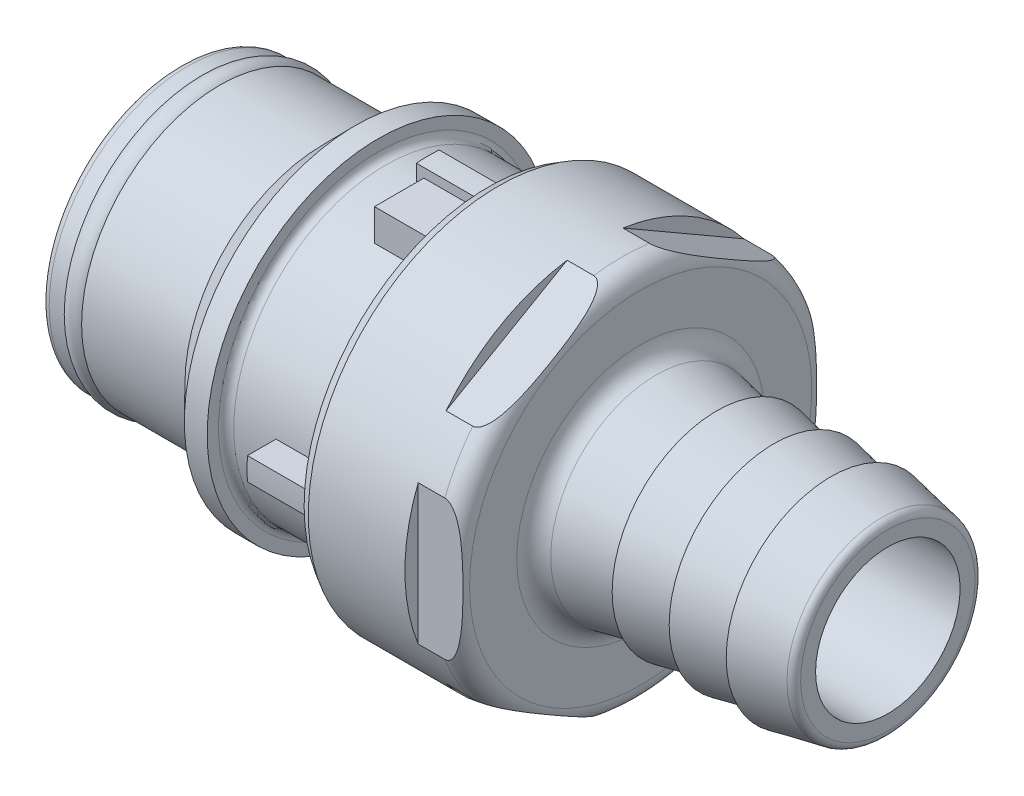
SolidWorks part; units mm, degrees
ref_plane "Front" through (0, 0, 0) normal (0, 0, 1) x (1, 0, 0)
ref_plane "Top" through (0, 0, 0) normal (0, 1, 0) x (1, 0, 0)
ref_plane "Right" through (0, 0, 0) normal (1, 0, 0) x (0, 0, -1)
ref_plane "Plane1" through (0, 0, 0) normal (0, 0, -1) x (-1, 0, 0)
sketch "Sketch1" plane through (0, 0, 0) normal (0, 0, -1) x (-1, 0, 0)
  line L0 (21.4503, 0) -> (19.6723, 0) construction
  arc A0 (19.6723, 8.7884) -> (21.4503, 8.7884) centre (20.5613, 9.0835) ccw
  arc A1 (21.4503, 8.7884) -> (19.6723, 8.7884) centre (20.5613, 8.5007) ccw
revolve "Revolve1" add sketch "Sketch1" angle 360 about L0
ref_plane "Plane2" through (0, 0, 0) normal (0, 0, -1) x (-1, 0, 0)
sketch "Sketch2" plane through (0, 0, 0) normal (0, 0, -1) x (-1, 0, 0)
  line L0 (0, 8.382) -> (9.558, 8.382)
  line L1 (9.558, 8.382) -> (9.558, 7.3614)
  line L2 (9.558, 7.3614) -> (11.7652, 7.3614)
  line L3 (11.7652, 7.3614) -> (12.2025, 6.604)
  line L4 (12.2025, 6.604) -> (22.6568, 6.604)
  line L5 (22.6568, 6.604) -> (22.6568, 8.7249)
  line L6 (22.1488, 9.2329) -> (13.081, 9.2329)
  line L7 (13.081, 9.2329) -> (10.922, 11.43)
  line L8 (10.922, 11.43) -> (9.398, 11.43)
  line L9 (9.398, 11.43) -> (9.398, 10.668)
  line L10 (8.89, 10.16) -> (3.302, 10.16)
  line L11 (2.032, 11.43) -> (2.032, 12.3187)
  line L12 (2.032, 12.3187) -> (1.3716, 12.7)
  line L13 (1.3716, 12.7) -> (0, 12.7)
  line L14 (0, 12.7) -> (0, 8.382)
  line L15 (22.6818, 0) -> (-22.225, 0) construction
  arc A0 (22.6568, 8.7249) -> (22.1488, 9.2329) centre (22.1488, 8.7249) ccw
  arc A1 (9.398, 10.668) -> (8.89, 10.16) centre (8.89, 10.668) cw
  arc A2 (3.302, 10.16) -> (2.032, 11.43) centre (3.302, 11.43) cw
revolve "Revolve2" add sketch "Sketch2" angle 360 about L15
ref_plane "Plane3" through (0, 0, 0) normal (0, 0, 1) x (1, 0, 0)
sketch "Sketch3" plane through (0, 0, 0) normal (0, 0, 1) x (1, 0, 0)
  line L0 (-25.4, 0) -> (-25.4, 2.159)
  line L1 (-25.4, 2.159) -> (-23.749, 2.159)
  line L2 (-21.717, 4.191) -> (-21.717, 4.572)
  line L3 (-21.336, 4.953) -> (-21.209, 4.953)
  line L4 (-21.209, 4.953) -> (-21.209, 3.8862)
  line L5 (-20.701, 3.3782) -> (-18.923, 3.3782)
  line L6 (-18.415, 3.8862) -> (-18.415, 5.6896)
  line L7 (-18.415, 5.6896) -> (-16.7132, 7.3914)
  line L8 (-16.7132, 7.3914) -> (-10.668, 7.3914)
  line L9 (-10.668, 7.3914) -> (-9.906, 8.1534)
  line L10 (-9.906, 8.1534) -> (0.254, 8.1534)
  line L11 (0.254, 8.1534) -> (0.254, 7.747)
  line L12 (0.254, 7.747) -> (-0.508, 6.985)
  line L13 (-0.508, 6.985) -> (-9.1443, 6.985)
  line L14 (-9.1443, 6.985) -> (-9.144, 5.715)
  line L15 (-9.144, 5.715) -> (-12.446, 5.715)
  line L16 (-12.446, 5.715) -> (-14.6002, 4.2066)
  line L17 (-14.2004, 1.9396) -> (-9.7088, 0.736)
  line L18 (-9.144, 0) -> (-25.4, 0)
  line L19 (-9.144, 0) -> (-25.4, 0) construction
  arc A0 (-23.749, 2.159) -> (-21.717, 4.191) centre (-23.749, 4.191) ccw
  arc A1 (-21.717, 4.572) -> (-21.336, 4.953) centre (-21.336, 4.572) cw
  arc A2 (-21.209, 3.8862) -> (-20.701, 3.3782) centre (-20.701, 3.8862) ccw
  arc A3 (-18.923, 3.3782) -> (-18.415, 3.8862) centre (-18.923, 3.8862) ccw
  arc A4 (-14.6002, 4.2066) -> (-14.2004, 1.9396) centre (-13.8717, 3.1663) ccw
  arc A5 (-9.7088, 0.736) -> (-9.144, 0) centre (-9.906, 0) cw
revolve "Revolve3" add sketch "Sketch3" angle 360 about L19
ref_plane "Plane4" through (-2.032, 0, 0) normal (-1, 0, 0) x (0, 0, 1)
sketch "Sketch4" plane through (-2.032, 0, 0) normal (-1, 0, 0) x (0, 0, 1)
  line L0 (-0.762, -10.1314) -> (-0.762, -12.0409)
  line L1 (0.762, -12.0409) -> (0.762, -10.1314)
  arc A0 (-0.762, -12.0409) -> (0.762, -12.0409) centre (0, 0) ccw
  arc A1 (0.762, -10.1314) -> (-0.762, -10.1314) centre (0, 0) cw
extrude "Boss-Extrude1" add sketch "Sketch4" along normal blind 4.064
ref_plane "Plane5" through (-2.032, 0, 0) normal (-1, 0, 0) x (0, 0, 1)
sketch "Sketch5" plane through (-2.032, 0, 0) normal (-1, 0, 0) x (0, 0, 1)
  line L0 (-12.0409, -0.762) -> (-10.1314, -0.762)
  line L1 (-10.1314, 0.762) -> (-12.0409, 0.762)
  arc A0 (-12.0409, 0.762) -> (-12.0409, -0.762) centre (0, 0) ccw
  arc A1 (-10.1314, -0.762) -> (-10.1314, 0.762) centre (0, 0) cw
extrude "Boss-Extrude2" add sketch "Sketch5" along normal blind 4.064
ref_plane "Plane6" through (-2.032, 0, 0) normal (-1, 0, 0) x (0, 0, 1)
sketch "Sketch6" plane through (-2.032, 0, 0) normal (-1, 0, 0) x (0, 0, 1)
  line L0 (4.064, 9.3118) -> (4.064, 11.43)
  line L1 (4.064, 11.43) -> (0.762, 11.43)
  line L2 (0.762, 11.43) -> (0.762, 12.0409)
  line L3 (-0.762, 12.0409) -> (-0.762, 10.1314)
  arc A0 (-0.762, 10.1314) -> (4.064, 9.3118) centre (0, 0) cw
  arc A1 (0.762, 12.0409) -> (-0.762, 12.0409) centre (0, 0) ccw
extrude "Boss-Extrude3" add sketch "Sketch6" along normal blind 3.556
ref_plane "Plane7" through (-2.032, 0, 0) normal (-1, 0, 0) x (0, 0, 1)
sketch "Sketch7" plane through (-2.032, 0, 0) normal (-1, 0, 0) x (0, 0, 1)
  line L0 (0.762, 10.1314) -> (0.762, 12.0409)
  line L1 (-0.762, 12.0409) -> (-0.762, 10.1314)
  arc A0 (-0.762, 10.1314) -> (0.762, 10.1314) centre (0, 0) cw
  arc A1 (0.762, 12.0409) -> (-0.762, 12.0409) centre (0, 0) ccw
extrude "Boss-Extrude4" add sketch "Sketch7" along normal blind 4.064
ref_plane "Plane8" through (-2.032, 0, 0) normal (-1, 0, 0) x (0, 0, 1)
sketch "Sketch8" plane through (-2.032, 0, 0) normal (-1, 0, 0) x (0, 0, 1)
  line L0 (10.1314, -0.762) -> (12.0409, -0.762)
  line L1 (12.0409, 0.762) -> (10.1314, 0.762)
  arc A0 (12.0409, -0.762) -> (12.0409, 0.762) centre (0, 0) ccw
  arc A1 (10.1314, 0.762) -> (10.1314, -0.762) centre (0, 0) cw
extrude "Boss-Extrude5" add sketch "Sketch8" along normal blind 4.064
ref_plane "Plane9" through (0, 0, 0) normal (0, -1, 0) x (1, 0, 0)
sketch "Sketch9" plane through (0, 0, 0) normal (0, -1, 0) x (1, 0, 0)
  line L0 (5.715, 4.826) -> (24.638, 4.826)
  line L1 (24.638, 4.826) -> (24.638, 5.8246)
  line L2 (24.2271, 6.3233) -> (20.828, 6.985)
  line L3 (20.828, 6.985) -> (20.828, 6.7056)
  line L4 (20.3742, 6.3316) -> (17.018, 6.985)
  line L5 (17.018, 6.985) -> (17.018, 6.7056)
  line L6 (16.5642, 6.3316) -> (13.208, 6.985)
  line L7 (13.208, 6.985) -> (13.208, 6.7056)
  line L8 (12.7542, 6.3316) -> (9.1553, 7.0322)
  line L9 (8.128, 8.2788) -> (8.128, 11.43)
  line L10 (6.858, 12.7) -> (0, 12.7)
  line L11 (0, 12.7) -> (0, 8.382)
  line L12 (0, 8.382) -> (3.302, 8.382)
  line L13 (3.302, 8.382) -> (3.302, 7.5565)
  line L14 (3.683, 7.1755) -> (5.207, 7.1755)
  line L15 (5.715, 6.6675) -> (5.715, 4.826)
  line L16 (24.663, 0) -> (0, 0) construction
  arc A0 (24.638, 5.8246) -> (24.2271, 6.3233) centre (24.13, 5.8246) ccw
  arc A1 (20.828, 6.7056) -> (20.3742, 6.3316) centre (20.447, 6.7056) cw
  arc A2 (17.018, 6.7056) -> (16.5642, 6.3316) centre (16.637, 6.7056) cw
  arc A3 (13.208, 6.7056) -> (12.7542, 6.3316) centre (12.827, 6.7056) cw
  arc A4 (9.1553, 7.0322) -> (8.128, 8.2788) centre (9.398, 8.2788) cw
  arc A5 (8.128, 11.43) -> (6.858, 12.7) centre (6.858, 11.43) ccw
  arc A6 (3.302, 7.5565) -> (3.683, 7.1755) centre (3.683, 7.5565) ccw
  arc A7 (5.207, 7.1755) -> (5.715, 6.6675) centre (5.207, 6.6675) cw
revolve "Revolve4" add sketch "Sketch9" angle 360 about L16
ref_plane "Plane10" through (5.08, 0, 0) normal (1, 0, 0) x (0, 0, -1)
sketch "Sketch10" plane through (5.08, 0, 0) normal (1, 0, 0) x (0, 0, -1)
  line L0 (-24.9961, 26.2247) -> (-24.9961, -28.0202)
  line L1 (-24.9961, -28.0202) -> (26.4137, -28.0202)
  line L2 (26.4137, -28.0202) -> (26.4137, 26.2247)
  line L3 (26.4137, 26.2247) -> (-24.9961, 26.2247)
  line L4 (-11.811, 6.8191) -> (-11.811, -6.8191)
  line L5 (-11.811, -6.8191) -> (0, -13.6382)
  line L6 (0, -13.6382) -> (11.811, -6.8191)
  line L7 (11.811, -6.8191) -> (11.811, 6.8191)
  line L8 (11.811, 6.8191) -> (0, 13.6382)
  line L9 (0, 13.6382) -> (-11.811, 6.8191)
extrude "Cut-Extrude1" cut sketch "Sketch10" along normal blind 10
